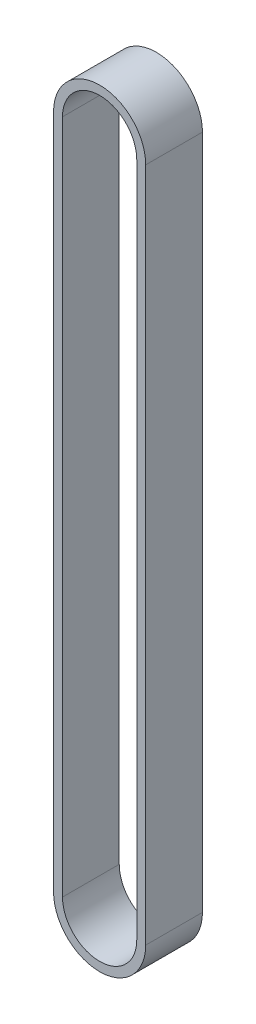
SolidWorks part; units mm, degrees
material "Natural Rubber"
ref_plane "Front" through (0, 0, 0) normal (0, 0, 1) x (1, 0, 0)
ref_plane "Top" through (0, 0, 0) normal (0, 1, 0) x (1, 0, 0)
ref_plane "Right" through (0, 0, 0) normal (1, 0, 0) x (0, 0, -1)
sketch "Sketch1" plane through (0, 0, 0) normal (0, 0, 1) x (1, 0, 0)
  line L0 (0, -113.1438) -> (0, 113.1438) construction
  line L1 (-12.4333, -113.1438) -> (-12.4333, 113.1438)
  line L2 (12.4333, -113.1438) -> (12.4333, 113.1438)
  line L3 (-15.4333, -113.1438) -> (-15.4333, 113.1438)
  line L4 (15.4333, -113.1438) -> (15.4333, 113.1438)
  arc A0 (-12.4333, -113.1438) -> (12.4333, -113.1438) centre (0, -113.1438) ccw
  arc A1 (12.4333, 113.1438) -> (-12.4333, 113.1438) centre (0, 113.1438) ccw
  arc A2 (15.4333, 113.1438) -> (-15.4333, 113.1438) centre (0, 113.1438) ccw
  arc A3 (-15.4333, -113.1438) -> (15.4333, -113.1438) centre (0, -113.1438) ccw
  point P2 (0, 0)
  dimension "D2" = 15.4333
  dimension "D3" = 12.4333
  dimension "D6" = 15.4333
  dimension "D1" = 226.2875
  dimension "D4" = 3
  dimension "D5" = 3
extrude "Boss-Extrude1" add sketch "Sketch1" along normal blind 19
